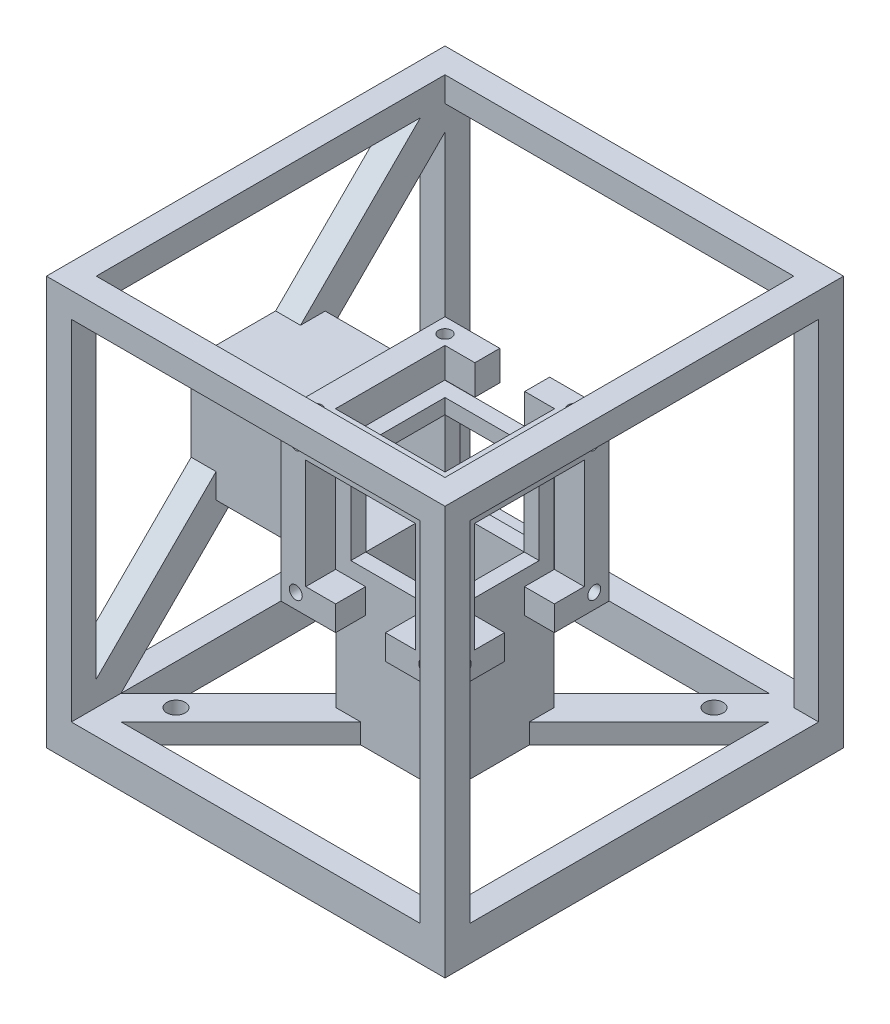
SolidWorks part; units mm, degrees
ref_plane "前视基准面" through (0, 0, 0) normal (0, 0, 1) x (1, 0, 0)
ref_plane "上视基准面" through (0, 0, 0) normal (0, 1, 0) x (1, 0, 0)
ref_plane "右视基准面" through (0, 0, 0) normal (1, 0, 0) x (0, 0, -1)
other "Configuration Table"
sketch "草图1" plane through (0, 0, 0) normal (0, 1, 0) x (1, 0, 0)
  line L0 (75, 75) -> (5, 5) construction
  line L1 (0, 0) -> (80, 0)
  line L2 (0, 0) -> (0, 80)
  line L3 (0, 80) -> (80, 80)
  line L4 (80, 0) -> (80, 80)
  line L5 (5, 5) -> (75, 5) construction
  line L6 (5, 5) -> (5, 75) construction
  line L7 (5, 75) -> (75, 75) construction
  line L8 (75, 5) -> (75, 75) construction
  line L9 (5, 75) -> (75, 5) construction
  line L10 (5, 9.9497) -> (29.0503, 34)
  line L11 (5, 70.0503) -> (29.0503, 46)
  line L12 (9.9497, 5) -> (34, 29.0503)
  line L13 (9.9497, 75) -> (34, 50.9497)
  line L14 (5, 40) -> (75, 40) construction
  line L15 (40, 5) -> (40, 75) construction
  line L16 (5, 70.0503) -> (5, 9.9497)
  line L17 (70.0503, 5) -> (9.9497, 5)
  line L18 (75, 9.9497) -> (75, 70.0503)
  line L19 (70.0503, 75) -> (9.9497, 75)
  line L20 (46, 29.0503) -> (70.0503, 5)
  line L21 (46, 50.9497) -> (70.0503, 75)
  line L22 (50.9497, 34) -> (75, 9.9497)
  line L23 (50.9497, 46) -> (75, 70.0503)
  line L24 (29.0503, 46) -> (29.0503, 34)
  line L29 (34, 50.9497) -> (46, 50.9497)
  line L30 (50.9497, 46) -> (50.9497, 34)
  line L31 (34, 29.0503) -> (46, 29.0503)
  line L33 (75, 5) -> (75, 0) construction
  circle A0 centre (13, 13) radius 1.85
  circle A1 centre (67, 13) radius 1.85
  circle A2 centre (67, 67) radius 1.85
  circle A3 centre (13, 67) radius 1.85
  point P9 (40, 0)
  dimension "D9" = 3.7
  dimension "D1" = 80
  dimension "D2" = 80
  dimension "D3" = 5
  dimension "D4" = 5
  dimension "D5" = 5
  dimension "D6" = 5
  dimension "D7" = 12
  dimension "D8" = 7
  dimension "D10" = 54
  dimension "D11" = 12
  dimension "D12" = 12
  dimension "D13" = 12
  dimension "D14" = 7
extrude "凸台-拉伸1" add sketch "草图1" along normal blind 7
sketch "草图6" plane through (0, 0, 0) normal (0, -1, 0) x (1, 0, 0)
  line L0 (75, -9.9497) -> (75, -70.0503) construction
  line L1 (5, -5) -> (75, -5)
  line L2 (5, -5) -> (5, -75)
  line L3 (5, -75) -> (75, -75)
  line L4 (0, 0) -> (0, -80)
  line L5 (0, -80) -> (80, -80)
  line L6 (80, -80) -> (80, 0)
  line L7 (80, 0) -> (0, 0)
  line L8 (0, 0) -> (0, -80)
  line L9 (0, -80) -> (80, -80)
  line L10 (80, -80) -> (80, 0)
  line L11 (80, 0) -> (0, 0)
  line L12 (75, -5) -> (75, -75)
  line L13 (70.0503, -75) -> (9.9497, -75) construction
  line L14 (5, -70.0503) -> (5, -9.9497) construction
  line L15 (9.9497, -5) -> (70.0503, -5) construction
  circle M9 centre (67, -67) radius 1.85
  circle M10 centre (13, -13) radius 1.85
  line M15 (29.0503, -46) -> (5, -70.0503)
  line M17 (5, -9.9497) -> (29.0503, -34)
  line M18 (9.9497, -75) -> (34, -50.9497)
  line M19 (46, -50.9497) -> (70.0503, -75)
  line M22 (70.0503, -5) -> (46, -29.0503)
  line M23 (34, -29.0503) -> (9.9497, -5)
  line M25 (75, -70.0503) -> (50.9497, -46)
  line M26 (50.9497, -34) -> (75, -9.9497)
  circle M27 centre (67, -13) radius 1.85
  circle M28 centre (13, -67) radius 1.85
  dimension "D1" = 0
extrude "切除-拉伸1" cut sketch "草图6" against normal blind 3 contours L12 L1 L2 L3 M22 M23 M17 M15 M18 M19 M25 M26 M10 M27 M28 M9
sketch "草图4" plane through (0, 7, 0) normal (0, 1, 0) x (1, 0, 0)
  line L1 (0, 80) -> (5, 80)
  line L2 (0, 80) -> (0, 75)
  line L3 (0, 75) -> (5, 75)
  line L4 (0, 80) -> (0, 0)
  line L5 (0, 0) -> (80, 0)
  line L6 (80, 0) -> (80, 80)
  line L7 (80, 80) -> (0, 80)
  line L8 (0, 80) -> (0, 0)
  line L9 (0, 0) -> (80, 0)
  line L10 (80, 0) -> (80, 80)
  line L11 (80, 80) -> (0, 80)
  line L12 (5, 80) -> (5, 75)
  line L13 (80, 80) -> (75, 80)
  line L14 (80, 80) -> (80, 75)
  line L15 (80, 75) -> (75, 75)
  line L16 (75, 80) -> (75, 75)
  line L17 (80, 0) -> (75, 0)
  line L18 (80, 0) -> (80, 5)
  line L19 (80, 5) -> (75, 5)
  line L20 (75, 0) -> (75, 5)
  line L21 (0, 0) -> (5, 0)
  line L22 (0, 0) -> (0, 5)
  line L23 (0, 5) -> (5, 5)
  line L24 (5, 0) -> (5, 5)
  line M24 (0, 0) -> (80, 0)
  line M25 (80, 0) -> (80, 80)
  line M26 (80, 80) -> (0, 80)
  dimension "D2" = 5
  dimension "D3" = 5
  dimension "D4" = 5
  dimension "D5" = 5
  dimension "D6" = 5
  dimension "D7" = 5
  dimension "D8" = 5
  dimension "D9" = 5
  dimension "D1" = 0
extrude "凸台-拉伸2" add sketch "草图4" along normal blind 70 contours L24 L23 L8 M24 | L20 L9 L19 M25 | L16 L15 L10 M26 | L1 L12 L3 L2
sketch "草图5" plane through (0, 77, 0) normal (0, 1, 0) x (1, 0, 0)
  line L1 (0, 80) -> (80, 80)
  line L2 (0, 80) -> (0, 0)
  line L3 (0, 0) -> (80, 0)
  line L4 (80, 80) -> (80, 0)
  line L5 (5, 75) -> (75, 75)
  line L6 (5, 75) -> (5, 5)
  line L7 (5, 5) -> (75, 5)
  line L8 (75, 75) -> (75, 5)
  line L12 (75, 80) -> (5, 80)
  line L13 (5, 80) -> (5, 75)
  line L14 (5, 75) -> (0, 75)
  line L15 (0, 75) -> (0, 5)
  line L16 (0, 5) -> (5, 5)
  line L17 (5, 5) -> (5, 0)
  line L18 (5, 0) -> (75, 0)
  line L19 (75, 0) -> (75, 5)
  line L20 (75, 5) -> (80, 5)
  line L21 (80, 5) -> (80, 75)
  line L22 (80, 75) -> (75, 75)
  line L23 (75, 75) -> (75, 80)
  line L24 (75, 80) -> (5, 80)
  line L27 (0, 75) -> (0, 5)
  line L30 (5, 0) -> (75, 0)
  line L33 (80, 5) -> (80, 75)
  line M17 (0, 0) -> (5, 0)
  line M18 (5, 0) -> (5, 5)
  line M19 (5, 5) -> (0, 5)
  line M20 (0, 5) -> (0, 0)
  dimension "D1" = 0
extrude "凸台-拉伸3" add sketch "草图5" along normal blind 5 contours L5 L8 L7 L3 L4 L1 L2 L6 M18 M19 | M20 M17 M18 M19
sketch "草图7" plane through (5, 0, 0) normal (1, 0, 0) x (0, 0, -1)
  line L1 (29.0503, 48) -> (29.0503, 36)
  line L5 (75, 7) -> (5, 77) construction
  line L6 (5, 7) -> (75, 77) construction
  line L7 (5, 72.0503) -> (29.0503, 48)
  line L8 (5, 77) -> (5, 7) construction
  line L9 (70.0503, 7) -> (9.9497, 7) construction
  line L10 (9.9497, 7) -> (34, 31.0503)
  line L11 (75, 77) -> (75, 7) construction
  line L12 (9.9497, 77) -> (34, 52.9497)
  line L13 (5, 11.9497) -> (29.0503, 36)
  line L14 (46, 52.9497) -> (70.0503, 77)
  line L15 (50.9497, 36) -> (75, 11.9497)
  line L16 (50.9497, 48) -> (75, 72.0503)
  line L17 (46, 31.0503) -> (70.0503, 7)
  line L18 (34, 31.0503) -> (46, 31.0503)
  line L19 (50.9497, 36) -> (50.9497, 48)
  line L20 (46, 52.9497) -> (34, 52.9497)
  line L21 (75, 7) -> (70.0503, 7)
  line L22 (75, 11.9497) -> (75, 7)
  line L23 (5, 11.9497) -> (5, 7)
  line L24 (5, 7) -> (9.9497, 7)
  line L25 (5, 72.0503) -> (5, 77)
  line L26 (5, 77) -> (9.9497, 77)
  line L27 (70.0503, 77) -> (75, 77)
  line L28 (75, 77) -> (75, 72.0503)
  dimension "D1" = 7
  dimension "D2" = 7
  dimension "D3" = 12
  dimension "D4" = 12
  dimension "D5" = 12
  dimension "D6" = 12
extrude "凸台-拉伸5" add sketch "草图7" against normal up to surface (5 mm away) up to face at (0, 41, -40)
sketch "草图8" plane through (0, 82, 0) normal (0, 1, 0) x (1, 0, 0)
  line L0 (75, 75) -> (75, 5) construction
  line L1 (5, 75) -> (5, 5) construction
  line L2 (5, 75) -> (75, 75) construction
  circle A0 centre (40, 40) radius 35
sketch "草图9" plane through (0, 0, 0) normal (0, 0, 1) x (1, 0, 0)
  line L0 (75, 77) -> (75, 7) construction
  line L1 (5, 77) -> (5, 7) construction
  line L2 (5, 77) -> (75, 77) construction
  circle A0 centre (40, 42) radius 35
sketch "草图10" plane through (80, 0, 0) normal (1, 0, 0) x (0, 0, -1)
  line L0 (75, 77) -> (75, 7) construction
  line L1 (5, 77) -> (5, 7) construction
  line L2 (75, 77) -> (5, 77) construction
  circle A0 centre (40, 42) radius 35
sketch "草图11" plane through (5, 0, 0) normal (1, 0, 0) x (0, 0, -1)
  line L0 (50.9497, 36) -> (50.9497, 48) construction
  line L1 (29.0503, 52.9497) -> (50.9497, 52.9497)
  line L2 (29.0503, 52.9497) -> (29.0503, 31.0503)
  line L3 (29.0503, 31.0503) -> (50.9497, 31.0503)
  line L4 (50.9497, 52.9497) -> (50.9497, 31.0503)
  line L5 (46, 52.9497) -> (34, 52.9497) construction
  line L6 (29.0503, 48) -> (29.0503, 36) construction
  line L7 (34, 31.0503) -> (46, 31.0503) construction
extrude "凸台-拉伸6" add sketch "草图11" along normal up to surface (45.9497 mm away) up to face at (50.9497, 5, -40)
sketch "草图12" plane through (0, 7, 0) normal (0, 1, 0) x (1, 0, 0)
  line L0 (46, 29.0503) -> (34, 29.0503) construction
  line L1 (29.0503, 29.0503) -> (50.9497, 29.0503)
  line L2 (29.0503, 29.0503) -> (29.0503, 50.9497)
  line L3 (29.0503, 50.9497) -> (50.9497, 50.9497)
  line L4 (50.9497, 29.0503) -> (50.9497, 50.9497)
  line L5 (50.9497, 46) -> (50.9497, 34) construction
  line L6 (34, 50.9497) -> (46, 50.9497) construction
  line L7 (29.0503, 34) -> (29.0503, 46) construction
extrude "凸台-拉伸7" add sketch "草图12" along normal up to surface (45.9497 mm away) up to face at (15.2374, 52.9497, -40)
sketch "草图16" plane through (0, 0, -29.0503) normal (0, 0, 1) x (1, 0, 0)
  line L1 (24, 58) -> (56, 58)
  line L2 (24, 58) -> (24, 26)
  line L3 (24, 26) -> (56, 26)
  line L4 (56, 58) -> (56, 26)
  line L5 (29, 53) -> (51, 53)
  line L6 (29, 53) -> (29, 31)
  line L7 (29, 31) -> (51, 31)
  line L8 (51, 53) -> (51, 31)
  dimension "D1" = 32
  dimension "D2" = 32
  dimension "D3" = 16
  dimension "D4" = 16
  dimension "D5" = 5
  dimension "D6" = 5
  dimension "D7" = 5
  dimension "D8" = 5
extrude "凸台-拉伸9" add sketch "草图16" along normal blind 6
sketch "草图18" plane through (50.9497, 0, 0) normal (1, 0, 0) x (0, 0, -1)
  line L1 (24, 58) -> (56, 58)
  line L2 (24, 58) -> (24, 26)
  line L3 (24, 26) -> (56, 26)
  line L4 (56, 58) -> (56, 26)
  line L5 (29, 53) -> (51, 53)
  line L6 (29, 53) -> (29, 31)
  line L7 (29, 31) -> (51, 31)
  line L8 (51, 53) -> (51, 31)
  dimension "D1" = 32
  dimension "D2" = 32
  dimension "D3" = 16
  dimension "D4" = 16
  dimension "D5" = 5
  dimension "D6" = 5
  dimension "D7" = 5
  dimension "D8" = 5
extrude "凸台-拉伸10" add sketch "草图18" along normal blind 6
sketch "草图19" plane through (0, 52.9497, 0) normal (0, 1, 0) x (1, 0, 0)
  line L1 (24, 56) -> (56, 56)
  line L2 (24, 56) -> (24, 24)
  line L3 (24, 24) -> (56, 24)
  line L4 (56, 56) -> (56, 24)
  line L5 (29, 51) -> (51, 51)
  line L6 (29, 51) -> (29, 29)
  line L7 (29, 29) -> (51, 29)
  line L8 (51, 51) -> (51, 29)
  dimension "D1" = 5
  dimension "D2" = 5
  dimension "D3" = 5
  dimension "D4" = 5
  dimension "D5" = 16
  dimension "D6" = 16
  dimension "D7" = 32
  dimension "D8" = 32
extrude "凸台-拉伸11" add sketch "草图19" along normal blind 6
sketch "草图20" plane through (0, 0, -23.0503) normal (0, 0, 1) x (1, 0, 0)
  line L0 (40, 42) -> (56, 42) construction
  line L2 (40, 42) -> (40, 23.6995) construction
  line L6 (29, 53) -> (29, 31) construction
  line L8 (24, 58) -> (24, 26) construction
  line L11 (45, 31) -> (35, 31)
  line L12 (29.0503, 31) -> (50.9497, 31) construction
  line L13 (29, 31) -> (51, 31) construction
  line L14 (35, 31) -> (35, 26)
  line L15 (24, 26) -> (56, 26) construction
  line L16 (35, 26) -> (45, 26)
  line L17 (45, 31) -> (45, 26)
  circle A0 centre (53, 29) radius 1.3
  circle A1 centre (27, 29) radius 1.3
  circle A2 centre (53, 55) radius 1.3
  circle A3 centre (27, 55) radius 1.3
  point P21 (29, 42)
  point P22 (24, 42)
  point P29 (40, 26)
  point P30 (40, 31)
  dimension "D1" = 2.6
  dimension "D2" = 26
  dimension "D3" = 26
  dimension "D4" = 5
extrude "切除-拉伸2" cut sketch "草图20" against normal up to surface (6 mm away) and the other way blind 2 up to face at (53.5, 41.9749, -29.0503)
sketch "草图21" plane through (56.9497, 0, 0) normal (1, 0, 0) x (0, 0, -1)
  line L0 (40, 42) -> (46.9642, 42) construction
  line L1 (40, 42) -> (40, 33.1563) construction
  line L2 (45, 31) -> (35, 31)
  line L3 (29, 31) -> (51, 31) construction
  line L4 (35, 31) -> (35, 26)
  line L5 (24, 26) -> (56, 26) construction
  line L6 (35, 26) -> (45, 26)
  line L7 (45, 31) -> (45, 26)
  circle A0 centre (53, 29) radius 1.3
  circle A1 centre (27, 29) radius 1.3
  circle A2 centre (27, 55) radius 1.3
  circle A3 centre (53, 55) radius 1.3
  point P21 (40, 26)
  point P22 (40, 31)
  dimension "D1" = 2.6
  dimension "D2" = 26
  dimension "D3" = 26
  dimension "D4" = 5
extrude "切除-拉伸3" cut sketch "草图21" against normal up to surface and the other way blind 2 up to face at (50.9497, 36.6499, -52.6499)
sketch "草图23" plane through (0, 58.9497, 0) normal (0, 1, 0) x (1, 0, 0)
  line L0 (40, 40) -> (46.9412, 40) construction
  line L1 (40, 40) -> (40, 48.2952) construction
  line L2 (35, 51) -> (45, 51)
  line L3 (51, 51) -> (29, 51) construction
  line L4 (45, 51) -> (45, 56)
  line L5 (56, 56) -> (24, 56) construction
  line L6 (45, 56) -> (35, 56)
  line L7 (35, 51) -> (35, 56)
  circle A0 centre (27, 53) radius 1.3
  circle A1 centre (53, 53) radius 1.3
  circle A2 centre (53, 27) radius 1.3
  circle A3 centre (27, 27) radius 1.3
  point P26 (40, 56)
  point P27 (40, 51)
  dimension "D1" = 2.6
  dimension "D2" = 26
  dimension "D3" = 26
  dimension "D4" = 5
extrude "切除-拉伸4" cut sketch "草图23" against normal up to surface and the other way blind 2 up to face at (34.6499, 52.9497, -52.6499)
sketch "草图25" plane through (0, 0, 0) normal (-1, 0, 0) x (0, 0, 1)
  line L1 (-32.0503, 49.9497) -> (-47.9497, 49.9497)
  line L2 (-32.0503, 49.9497) -> (-32.0503, 34.0503)
  line L3 (-32.0503, 34.0503) -> (-47.9497, 34.0503)
  line L4 (-47.9497, 49.9497) -> (-47.9497, 34.0503)
  line L5 (-34, 52.9497) -> (-46, 52.9497) construction
  line L6 (-29.0503, 36) -> (-29.0503, 48) construction
  line L7 (-46, 31.0503) -> (-34, 31.0503) construction
  line L8 (-50.9497, 48) -> (-50.9497, 36) construction
  line L10 (-29.0503, 52.9497) -> (-50.9497, 52.9497)
  line L11 (-29.0503, 52.9497) -> (-29.0503, 31.0503)
  line L12 (-29.0503, 31.0503) -> (-50.9497, 31.0503)
  line L13 (-50.9497, 52.9497) -> (-50.9497, 31.0503)
  dimension "D1" = 3
  dimension "D2" = 3
  dimension "D3" = 3
  dimension "D4" = 3
extrude "切除-拉伸5" cut sketch "草图25" against normal up to surface (50.9497 mm away) contours L2 L1 L4 L3 up to face at (50.9497, 22.9937, -40)
sketch "草图26" plane through (0, 3, 0) normal (0, -1, 0) x (1, 0, 0)
  line L0 (46, -29.0503) -> (34, -29.0503) construction
  line L1 (47.9497, -32.0503) -> (32.0503, -32.0503)
  line L2 (47.9497, -32.0503) -> (47.9497, -47.9497)
  line L3 (47.9497, -47.9497) -> (32.0503, -47.9497)
  line L4 (32.0503, -32.0503) -> (32.0503, -47.9497)
  line L5 (50.9497, -46) -> (50.9497, -34) construction
  line L6 (34, -50.9497) -> (46, -50.9497) construction
  line L7 (29.0503, -50.9497) -> (29.0503, -29.0503) construction
  dimension "D1" = 3
  dimension "D2" = 3
  dimension "D3" = 3
  dimension "D4" = 3
extrude "切除-拉伸6" cut sketch "草图26" against normal up to surface (49.9497 mm away) up to face at (39.9749, 52.9497, -40)
sketch "草图27" plane through (0, 0, -29.0503) normal (0, 0, 1) x (1, 0, 0)
  line L0 (24, 52.9497) -> (5, 52.9497) construction
  line L1 (32.0503, 49.9497) -> (47.9497, 49.9497)
  line L2 (32.0503, 49.9497) -> (32.0503, 34.0503)
  line L3 (32.0503, 34.0503) -> (47.9497, 34.0503)
  line L4 (47.9497, 49.9497) -> (47.9497, 34.0503)
  line L5 (24, 31.0503) -> (5, 31.0503) construction
  line L6 (50.9497, 26) -> (50.9497, 7) construction
  line L7 (29.0503, 26) -> (29.0503, 7) construction
  dimension "D1" = 3
  dimension "D2" = 3
  dimension "D3" = 3
  dimension "D4" = 3
extrude "切除-拉伸7" cut sketch "草图27" against normal up to surface (21.8995 mm away) up to face at (27.4944, 29.6055, -50.9497)
